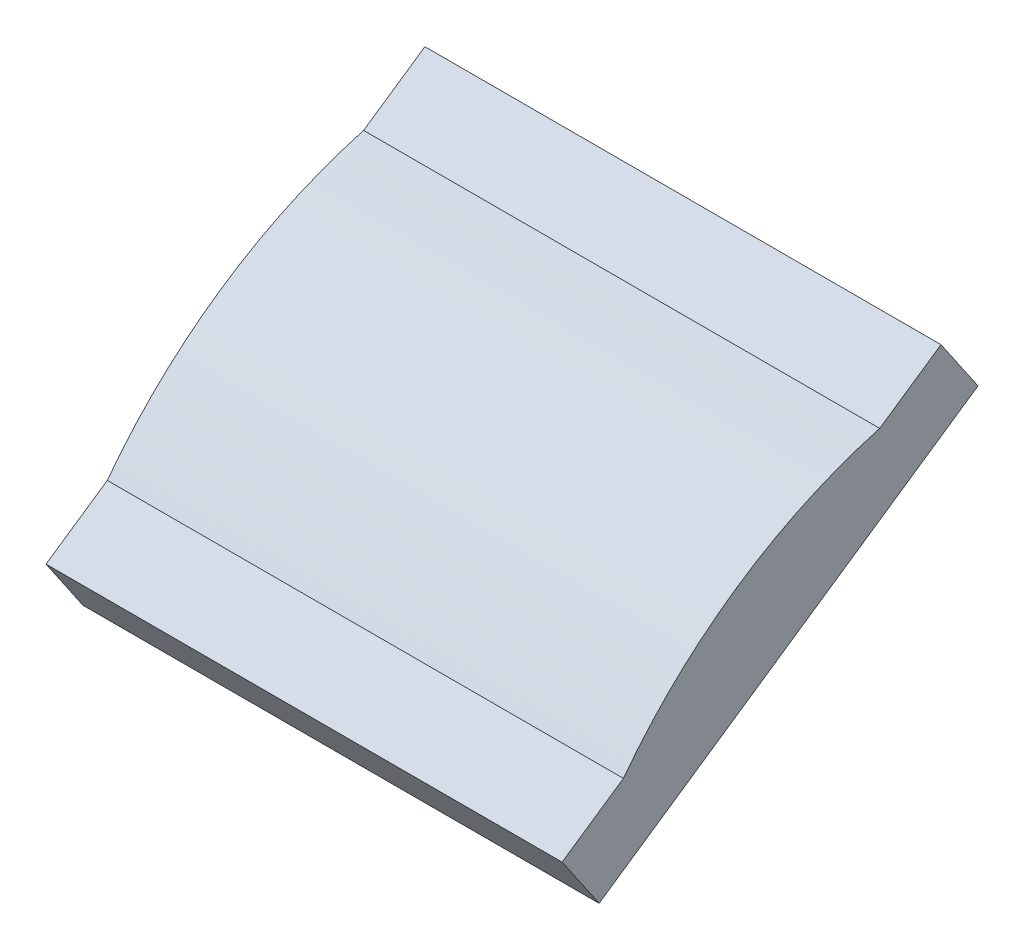
SolidWorks part; units mm, degrees
ref_plane "Plano frontal" through (0, 0, 0) normal (0, 0, 1) x (1, 0, 0)
ref_plane "Plano superior" through (0, 0, 0) normal (0, 1, 0) x (1, 0, 0)
ref_plane "Plano direito" through (0, 0, 0) normal (1, 0, 0) x (0, 0, -1)
sketch "Esboço2" plane through (0, 0, 0) normal (1, 0, 0) x (0, 0, -1)
  line L2 (16.5264, 22.8149) -> (-37.3011, -13.9415)
  line L3 (16.5264, 22.8149) -> (-11.048, 3.9855) construction
  line L4 (16.5264, 22.8149) -> (-11.048, 3.9855)
  line L5 (-11.048, 3.9855) -> (-3.1346, 45.9764)
  line L8 (27.0449, -7.661) -> (16.5264, 22.8149)
  line L9 (-36.527, -16.1844) -> (24.0227, -12.2095)
  line L10 (92.0711, 114.8307) -> (95.7876, 117.368)
  line L11 (1.4152, 52.9359) -> (92.0711, 114.8307)
  line L12 (92.8967, 113.9194) -> (16.5264, 22.8149)
  line L13 (92.8967, 113.9194) -> (95.7876, 117.368)
  line L14 (-2.3012, 50.3985) -> (-3.1346, 45.9764)
  line L15 (1.4152, 52.9359) -> (-2.3012, 50.3985)
  circle A0 centre (-41.0173, -16.4792) radius 2.5
  circle A1 centre (28.5131, -11.9148) radius 2.5
  arc A4 (-37.3011, -13.9415) -> (-36.527, -16.1844) centre (-41.0173, -16.4792) ccw
  arc A5 (24.0227, -12.2095) -> (27.0449, -7.661) centre (28.5131, -11.9148) ccw
  dimension "D14" = 5
  dimension "D15" = 2
  dimension "D16" = 5
  dimension "D17" = 2
  dimension "D1" = 69.68
  dimension "D2" = 36.74
  dimension "D3" = 69.68
  dimension "D7" = 33.39
  dimension "D8" = 47.23
  dimension "D9" = 118.77
  dimension "D10" = 123.38
  dimension "D11" = 135
extrude "Ressalto-extrusão2" add sketch "Esboço2" along normal blind 5
sketch "Esboço3" plane through (5, 0, 0) normal (1, 0, 0) x (0, 0, -1)
  line L0 (-2.3012, 50.3985) -> (-234.561, -108.1754)
  line L1 (-2.3012, 50.3985) -> (95.7876, 117.368) construction
  line L2 (-234.561, -108.1754) -> (-266.8137, -60.9356)
  line L3 (95.7876, 117.368) -> (63.5348, 164.6079)
  line L4 (-234.561, -108.1754) -> (-69.3867, 4.5963) construction
  line L5 (-69.3867, 4.5963) -> (-169.5841, 151.3533) construction
  line L6 (-266.8137, -60.9356) -> (-213.3633, -24.4427)
  line L7 (-69.3867, 4.5963) -> (-114.2473, 70.3026) construction
  line L8 (63.5348, 164.6079) -> (10.0845, 128.1149)
  line L9 (-2.3012, 50.3985) -> (95.7876, 117.368)
  arc A0 (-213.3633, -24.4427) -> (10.0845, 128.1149) centre (121.5838, -275.1139) cw
  point P15 (-114.2473, 70.3026)
  dimension "D1" = 180
  dimension "D2" = 400
  dimension "D3" = 90
  dimension "D4" = 90
  dimension "D5" = 57.2
  dimension "D6" = 57.2
  dimension "D7" = 64.72
  dimension "D8" = 64.72
extrude "Ressalto-extrusão3" add sketch "Esboço3" along normal blind 173.55 separate body
sketch "Esboço4" plane through (5, 0, 0) normal (-1, 0, 0) x (0, 0, 1)
  line L0 (234.561, -108.1754) -> (-95.7876, 117.368)
  line L1 (-95.7876, 117.368) -> (-63.5348, 164.6079)
  line L2 (-63.5348, 164.6079) -> (-10.0845, 128.1149)
  line L3 (234.561, -108.1754) -> (266.8137, -60.9356)
  line L4 (266.8137, -60.9356) -> (213.3633, -24.4427)
  arc A0 (213.3633, -24.4427) -> (-10.0845, 128.1149) centre (-121.5838, -275.1139) ccw construction
  arc A1 (-10.0845, 128.1149) -> (213.3633, -24.4427) centre (-121.5838, -275.1139) cw
  point P4 (114.3125, 70.3981)
extrude "Ressalto-extrusão4" add sketch "Esboço4" along normal blind 276.45
